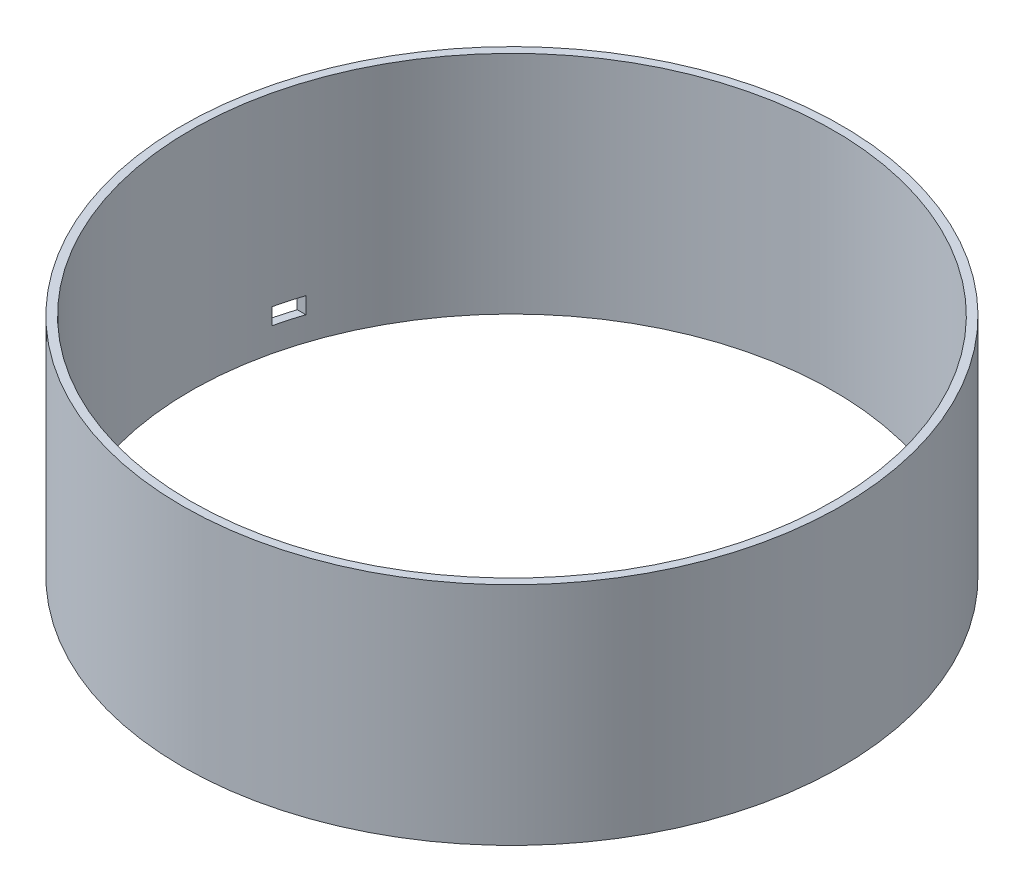
SolidWorks part; units mm, degrees
ref_plane "Front Plane" through (0, 0, 0) normal (0, 0, 1) x (1, 0, 0)
ref_plane "Top Plane" through (0, 0, 0) normal (0, 1, 0) x (1, 0, 0)
ref_plane "Right Plane" through (0, 0, 0) normal (1, 0, 0) x (0, 0, -1)
sketch "Sketch1" plane through (0, 0, 0) normal (0, 1, 0) x (1, 0, 0)
  circle A0 centre (0, 0) radius 200
  circle A1 centre (0, 0) radius 195
  dimension "D1" = 400
  dimension "D2" = 5
extrude "Boss-Extrude1" add sketch "Sketch1" along normal blind 137
ref_plane "Plane1" through (-200, 0, 0) normal (1, 0, 0) x (0, 0, -1)
sketch "Sketch2" plane through (-200, 0, 0) normal (1, 0, 0) x (0, 0, -1)
  line L1 (44.3782, 14.621) -> (60.3782, 14.621)
  line L2 (44.3782, 14.621) -> (44.3782, 24.621)
  line L3 (44.3782, 24.621) -> (60.3782, 24.621)
  line L4 (60.3782, 14.621) -> (60.3782, 24.621)
  dimension "D1" = 10
  dimension "D2" = 16
  dimension "D3" = 44.3782
  dimension "D4" = 14.621
extrude "Cut-Extrude1" cut sketch "Sketch2" against normal mid plane 141
